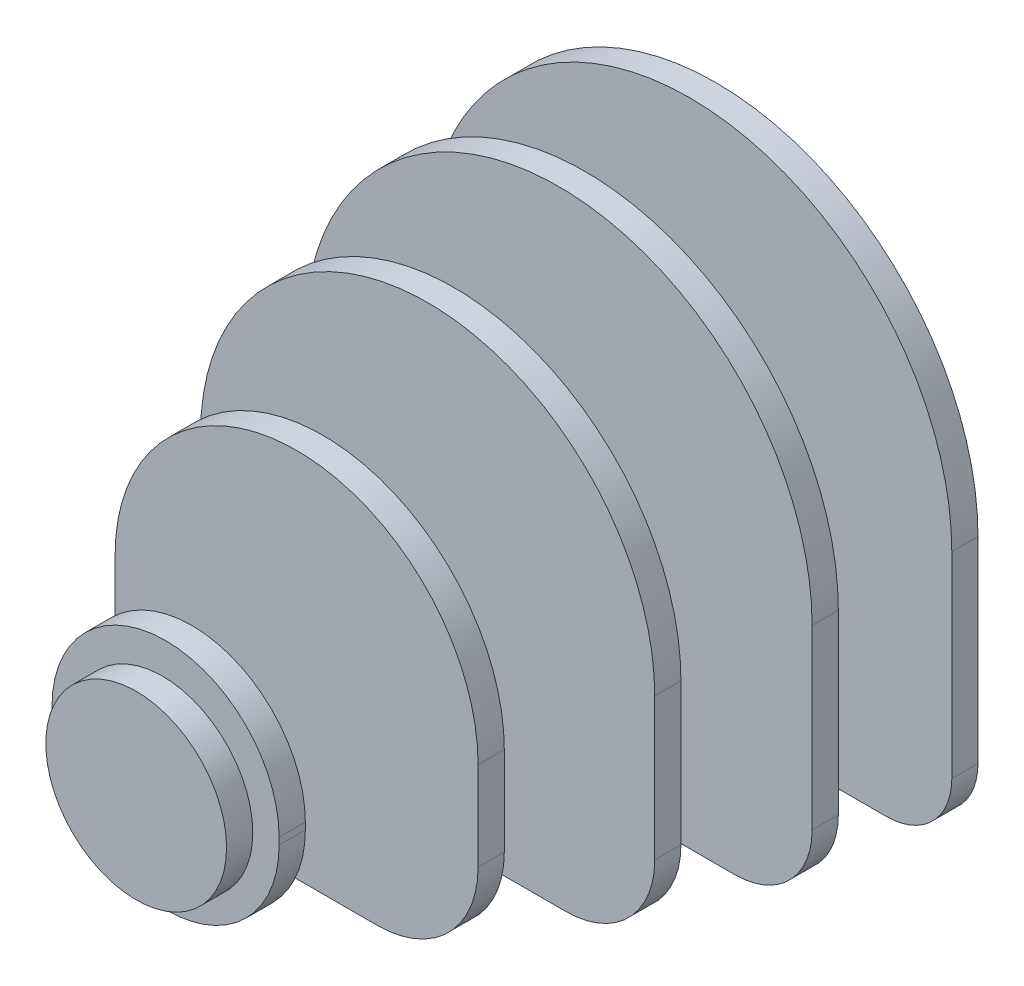
SolidWorks part; units mm, degrees
ref_plane "Front Plane" through (0, 0, 0) normal (0, 0, 1) x (1, 0, 0)
ref_plane "Top Plane" through (0, 0, 0) normal (0, 1, 0) x (1, 0, 0)
ref_plane "Right Plane" through (0, 0, 0) normal (1, 0, 0) x (0, 0, -1)
ref_plane "Plane1" through (0, -25, 0) normal (0, 1, 0) x (1, 0, 0)
sketch "Sketch1" plane through (0, 0, 0) normal (0, 0, 1) x (1, 0, 0)
  line L0 (100, 0) -> (100, -75)
  line L1 (27.5, 0) -> (-27.5, 0) construction
  line L2 (75, -100) -> (-75, -100)
  line L3 (0, -27.5) -> (0, 27.5) construction
  line L4 (0, 100) -> (0, -100) construction
  line L5 (-100, 0) -> (-100, -75)
  arc A0 (100, -75) -> (75, -100) centre (75, -75) cw
  arc A1 (100, 0) -> (-100, 0) centre (0, 0) ccw
  arc A2 (-100, -75) -> (-75, -100) centre (-75, -75) ccw
  dimension "D1" = 100
  dimension "D3" = 25
  dimension "D2" = 100
sketch "Sketch2" plane through (0, 0, 0) normal (1, 0, 0) x (0, 0, -1)
  line L0 (0, 100) -> (0, -100) construction
  line L1 (-225, -25) -> (0, -25) construction
  line L2 (0, 0) -> (0, -75) construction
  arc A0 (0, 100) -> (-211.2069, 9.4828) centre (0, -191.6667) ccw
  arc A1 (-211.2069, 9.4828) -> (-189, -73) centre (-175, -25) ccw
  arc A2 (-189, -73) -> (0, -100) centre (0, 575) ccw
  dimension "D1" = 50
  dimension "D2" = 225
  dimension "D3" = 75
sketch "Sketch3" plane through (0, -25, 0) normal (0, 1, 0) x (1, 0, 0)
  arc A0 (42.4528, -201.4151) -> (-42.4528, -201.4151) centre (0, -175) cw
  arc A1 (-100, 0) -> (-42.4528, -201.4151) centre (281.25, 0) ccw
  arc A2 (100, 0) -> (42.4528, -201.4151) centre (-281.25, 0) cw
ref_plane "Plane2" through (0, 0, 50) normal (0, 0, 1) x (1, 0, 0)
ref_plane "Plane3" through (0, 0, 100) normal (0, 0, 1) x (1, 0, 0)
ref_plane "Plane4" through (0, 0, 150) normal (0, 0, 1) x (1, 0, 0)
ref_plane "Plane5" through (0, 0, 200) normal (0, 0, 1) x (1, 0, 0)
sketch "Sketch4" plane through (0, 0, 50) normal (0, 0, 1) x (1, 0, 0)
  line L0 (96.7071, -1.0248) -> (96.7071, -68.6456)
  line L7 (67.2071, -98.1456) -> (-67.2071, -98.1456)
  line L8 (0, 95.6823) -> (0, -98.1456) construction
  line L9 (-96.7071, -1.0248) -> (-96.7071, -68.6456)
  arc A0 (96.7071, -1.0248) -> (-96.7071, -1.0248) centre (0, -1.0248) ccw
  arc A1 (96.7071, -68.6456) -> (67.2071, -98.1456) centre (67.2071, -68.6456) cw
  arc A2 (-96.7071, -68.6456) -> (-67.2071, -98.1456) centre (-67.2071, -68.6456) ccw
  point P5 (96.7071, -25)
  point P6 (0, 95.6823)
  point P7 (0, -98.1456)
  dimension "D1" = 29.5
sketch "Sketch5" plane through (0, 0, 100) normal (0, 0, 1) x (1, 0, 0)
  line L0 (0, 100) -> (0, -100) construction
  line L1 (86.6516, -4.3302) -> (86.6516, -58.5515)
  line L2 (52.6516, -92.5515) -> (-52.6516, -92.5515)
  line L9 (0, 82.3214) -> (0, -92.5515) construction
  line L10 (-86.6516, -4.3302) -> (-86.6516, -58.5515)
  arc A0 (86.6516, -4.3302) -> (-86.6516, -4.3302) centre (0, -4.3302) ccw
  arc A1 (86.6516, -58.5515) -> (52.6516, -92.5515) centre (52.6516, -58.5515) cw
  arc A2 (-86.6516, -58.5515) -> (-52.6516, -92.5515) centre (-52.6516, -58.5515) ccw
  point P8 (86.6516, -25)
  point P10 (0, 82.3214)
  point P12 (0, -92.5515)
  dimension "D1" = 34
sketch "Sketch6" plane through (0, 0, 150) normal (0, 0, 1) x (1, 0, 0)
  line L0 (-30.7519, -83.1223) -> (30.7519, -83.1223)
  line L1 (69.2519, -44.6223) -> (69.2519, -10.7797)
  line L8 (0, 58.4722) -> (0, -83.1223) construction
  line L9 (-69.2519, -44.6223) -> (-69.2519, -10.7797)
  arc A0 (30.7519, -83.1223) -> (69.2519, -44.6223) centre (30.7519, -44.6223) ccw
  arc A1 (69.2519, -10.7797) -> (-69.2519, -10.7797) centre (0, -10.7797) ccw
  arc A2 (-30.7519, -83.1223) -> (-69.2519, -44.6223) centre (-30.7519, -44.6223) cw
  point P7 (69.2519, -25)
  point P8 (0, 58.4722)
  point P10 (0, -83.1223)
  dimension "D1" = 38.5
sketch "Sketch7" plane through (0, 0, 200) normal (0, 0, 1) x (1, 0, 0)
  line L0 (-0.3291, -68.3013) -> (0.3291, -68.3013)
  line L1 (43.3291, -25.3013) -> (43.3291, -22.7001)
  line L9 (0, 20.629) -> (0, -68.3013) construction
  line L10 (-43.3291, -25.3013) -> (-43.3291, -22.7001)
  arc A0 (0.3291, -68.3013) -> (43.3291, -25.3013) centre (0.3291, -25.3013) ccw
  arc A1 (43.3291, -22.7001) -> (-43.3291, -22.7001) centre (0, -22.7001) ccw
  arc A2 (-0.3291, -68.3013) -> (-43.3291, -25.3013) centre (-0.3291, -25.3013) cw
  point P7 (0, 20.629)
  point P8 (43.3291, -25)
  point P10 (0, -68.3013)
  dimension "D1" = 43
ref_plane "Plane6" through (0, 0, 211.2069) normal (0, 0, 1) x (1, 0, 0)
sketch "Sketch8" plane through (0, 0, 211.2069) normal (0, 0, 1) x (1, 0, 0)
  circle A0 centre (0, -25) radius 34.4828
  point P2 (0, -59.4828)
sketch "Sketch9" plane through (0, 0, 0) normal (1, 0, 0) x (0, 0, -1)
  line L0 (0, -25) -> (0, 0)
  line L1 (0, 100) -> (0, -100) construction
  line L2 (0, 0) -> (-200, 18)
  line L3 (-200, 18) -> (-200, -25)
  line L5 (-200, 20.629) -> (-200, -22.7001) construction
  line L6 (-50, -25) -> (-50, 4.5)
  line L7 (-100, -25) -> (-100, 9)
  line L8 (-150, -25) -> (-150, 13.5)
  dimension "D1" = 43
  dimension "D2" = 25
  dimension "D3" = 29.5
  dimension "D4" = 34
  dimension "D5" = 38.5
extrude "Boss-Extrude1" add sketch "Sketch1" along normal blind 10 contours A1 L5 A2 L2 A0 L0
extrude "Boss-Extrude2" add sketch "Sketch4" along normal blind 10 separate body contours A0 L9 A2 L7 A1 L0
extrude "Boss-Extrude3" add sketch "Sketch5" along normal blind 10 separate body contours A0 L10 A2 L2 A1 L1
extrude "Boss-Extrude4" add sketch "Sketch6" along normal blind 10 separate body contours A1 L9 A2 L0 A0 L1
extrude "Boss-Extrude5" add sketch "Sketch7" along normal blind 10 separate body contours A1 L10 A2 L0 A0 L1
extrude "Boss-Extrude6" add sketch "Sketch8" along normal blind 10 separate body contours A0
